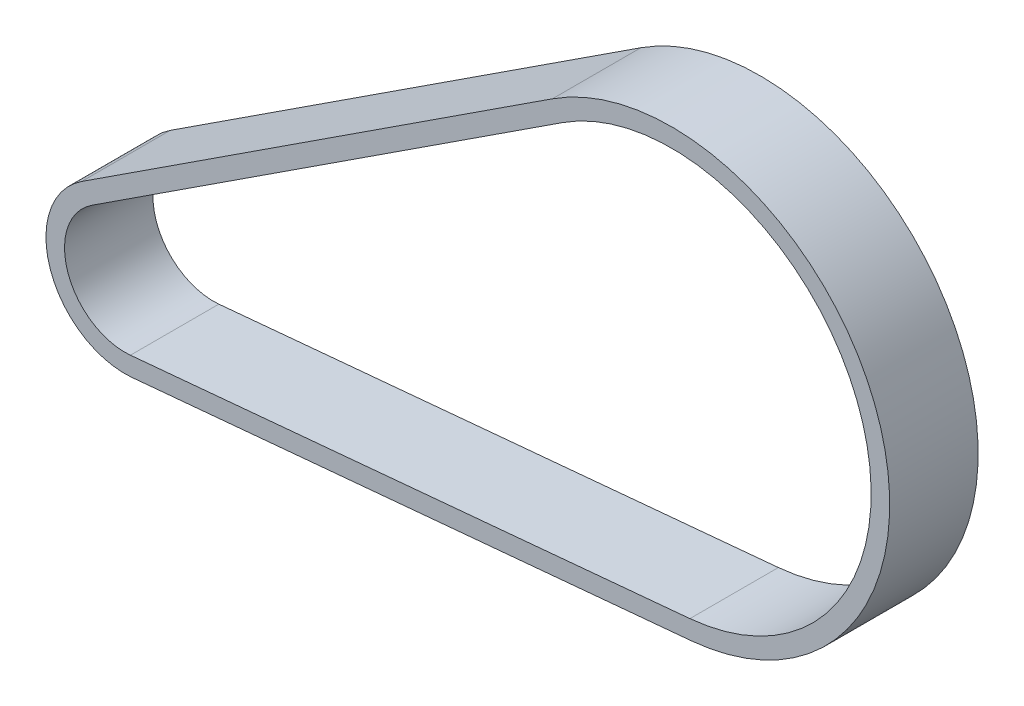
SolidWorks part; units mm, degrees
material "BUTYL"
ref_plane "Plano frontal" through (0, 0, 0) normal (0, 0, 1) x (1, 0, 0)
ref_plane "Plano superior" through (0, 0, 0) normal (0, 1, 0) x (1, 0, 0)
ref_plane "Plano direito" through (0, 0, 0) normal (1, 0, 0) x (0, 0, -1)
sketch "Esboço2" plane through (0, 0, 0) normal (0, 0, 1) x (1, 0, 0)
  line L0 (0, 0) -> (1, 0) construction
  line L1 (0, 0) -> (0, 1) construction
  line L2 (2.1598, -23.4005) -> (-58.1188, -28.964)
  line L3 (-63.5428, -13.38) -> (-12.8359, 19.6847)
  arc A0 (-12.8359, 19.6847) -> (2.1598, -23.4005) centre (0, 0) cw
  arc A1 (-58.1188, -28.964) -> (-63.5428, -13.38) centre (-58.9, -20.5) cw
extrude "Extrusão-Fina1" add sketch "Esboço2" along normal blind 9.53 thin
